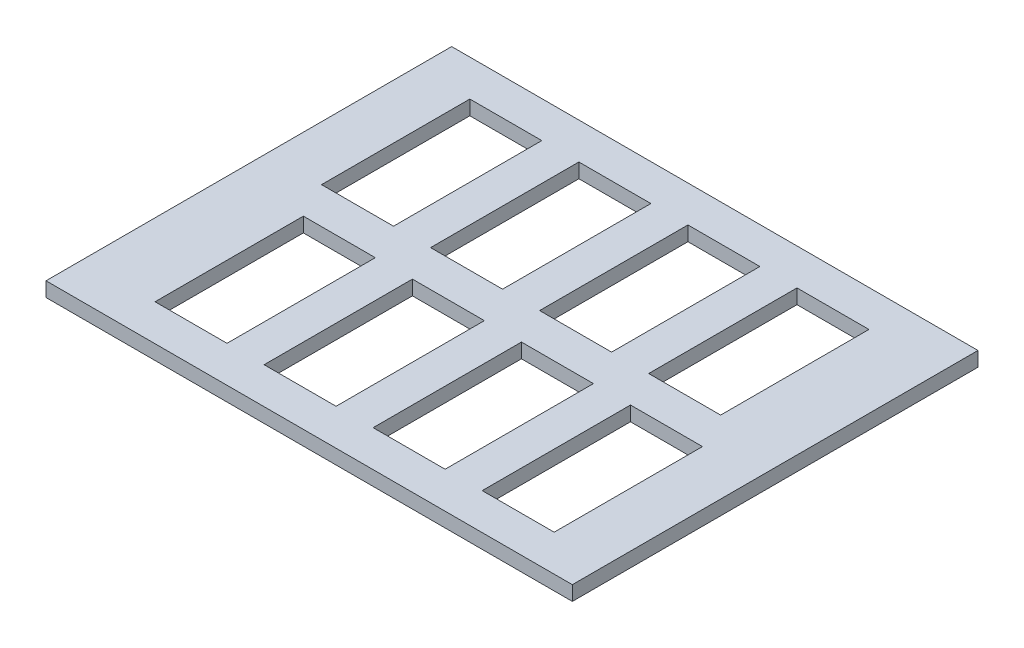
SolidWorks part; units mm, degrees
ref_plane "Front Plane" through (0, 0, 0) normal (0, 0, 1) x (1, 0, 0)
ref_plane "Top Plane" through (0, 0, 0) normal (0, 1, 0) x (1, 0, 0)
ref_plane "Right Plane" through (0, 0, 0) normal (1, 0, 0) x (0, 0, -1)
sketch "Sketch2" plane through (0, 0, 0) normal (0, 1, 0) x (1, 0, 0)
  line L0 (106.5749, -182.3572) -> (106.5749, -70.7572) construction
  line L1 (-72.4, 55.8) -> (72.4, 55.8)
  line L2 (-72.4, 55.8) -> (-72.4, -55.8)
  line L3 (-72.4, -55.8) -> (72.4, -55.8)
  line L4 (72.4, 55.8) -> (72.4, -55.8)
  line L5 (-72.4, 55.8) -> (72.4, -55.8) construction
  line L6 (-72.4, -55.8) -> (72.4, 55.8) construction
  line L8 (-38.2251, -182.3572) -> (106.5749, -182.3572) construction
  line L9 (0, 0) -> (-81.9061, 0) construction
  line L10 (-18.2251, -131.5572) -> (1.5749, -131.5572) construction
  line L11 (-52.4, -5) -> (-32.6, -5)
  line L12 (-52.4, -5) -> (-52.4, -45.8)
  line L13 (-52.4, -45.8) -> (-32.6, -45.8)
  line L14 (-32.6, -5) -> (-32.6, -45.8)
  line L15 (-18.2251, -131.5572) -> (-18.2251, -172.3572) construction
  line L16 (-22.4, -5) -> (-22.4, -45.8)
  line L17 (-22.4, -5) -> (-2.6, -5)
  line L18 (-2.6, -5) -> (-2.6, -45.8)
  line L19 (-22.4, -45.8) -> (-2.6, -45.8)
  line L20 (7.6, -5) -> (7.6, -45.8)
  line L21 (7.6, -5) -> (27.4, -5)
  line L22 (27.4, -5) -> (27.4, -45.8)
  line L23 (7.6, -45.8) -> (27.4, -45.8)
  line L24 (37.6, -5) -> (37.6, -45.8)
  line L25 (37.6, -5) -> (57.4, -5)
  line L26 (57.4, -5) -> (57.4, -45.8)
  line L27 (37.6, -45.8) -> (57.4, -45.8)
  line L28 (-52.4, -5) -> (-22.4, -5) construction
  line L29 (-18.2251, -131.5572) -> (11.7749, -131.5572) construction
  line L30 (-57.4, 45.8) -> (-37.6, 45.8)
  line L31 (-57.4, 45.8) -> (-57.4, 5)
  line L32 (-57.4, 5) -> (-37.6, 5)
  line L33 (-37.6, 45.8) -> (-37.6, 5)
  line L34 (-27.4, 45.8) -> (-7.6, 45.8)
  line L35 (-7.6, 45.8) -> (-7.6, 5)
  line L36 (-27.4, 5) -> (-7.6, 5)
  line L37 (-27.4, 45.8) -> (-27.4, 5)
  line L38 (2.6, 45.8) -> (22.4, 45.8)
  line L39 (22.4, 45.8) -> (22.4, 5)
  line L40 (2.6, 5) -> (22.4, 5)
  line L41 (2.6, 45.8) -> (2.6, 5)
  line L42 (32.6, 45.8) -> (52.4, 45.8)
  line L43 (52.4, 45.8) -> (52.4, 5)
  line L44 (32.6, 5) -> (52.4, 5)
  line L45 (32.6, 45.8) -> (32.6, 5)
  line L46 (-57.4, 45.8) -> (-27.4, 45.8) construction
  line L47 (-52.4, -5) -> (-72.4, -5) construction
  line L48 (-72.4, -5) -> (-52.4, -5) construction
  line L49 (-52.4, -5) -> (-52.4, 0) construction
  line L50 (-18.2251, -131.5572) -> (-38.2251, -131.5572) construction
  line L51 (-18.2251, -131.5572) -> (-18.2251, -126.5572) construction
  line L52 (-57.4, 5) -> (-72.4, 5) construction
  line L53 (-23.2251, -121.5572) -> (-38.2251, -121.5572) construction
  point P0 (0, 0)
  point P63 (-34.7308, 38.9957)
  point P64 (-35.0262, 49.4832)
  dimension "D1" = 4
  dimension "D3" = 4
extrude "Boss-Extrude1" add sketch "Sketch2" along normal blind 4
